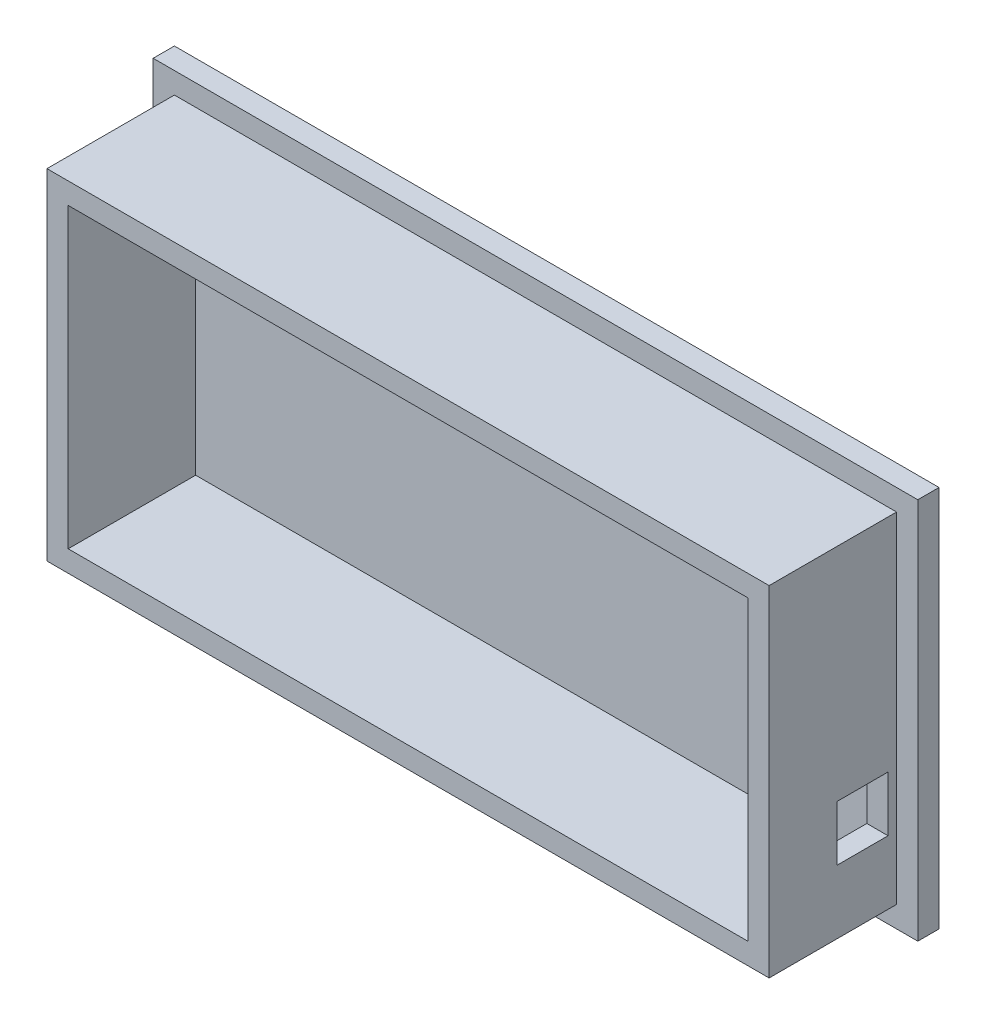
SolidWorks part; units mm, degrees
ref_plane "Plan de face" through (0, 0, 0) normal (0, 0, 1) x (1, 0, 0)
ref_plane "Plan de dessus" through (0, 0, 0) normal (0, 1, 0) x (1, 0, 0)
ref_plane "Plan de droite" through (0, 0, 0) normal (1, 0, 0) x (0, 0, -1)
sketch "Esquisse2" plane through (0, 0, 0) normal (0, 0, 1) x (1, 0, 0)
  line L1 (0, 0) -> (180, 0)
  line L2 (0, 0) -> (0, 90)
  line L3 (0, 90) -> (180, 90)
  line L4 (180, 0) -> (180, 90)
  dimension "D1" = 180
  dimension "D2" = 90
extrude "Boss.-Extru.2" add sketch "Esquisse2" along normal blind 5
sketch "Esquisse3" plane through (0, 0, 5) normal (0, 0, 1) x (1, 0, 0)
  line L4 (170, 80) -> (10, 80)
  line L5 (10, 80) -> (10, 10)
  line L6 (10, 10) -> (170, 10)
  line L7 (170, 10) -> (170, 80)
  line L8 (5, 85) -> (5, 5)
  line L9 (5, 5) -> (175, 5)
  line L10 (175, 5) -> (175, 85)
  line L11 (175, 85) -> (5, 85)
  line L12 (5, 85) -> (5, 5)
  line L13 (5, 5) -> (175, 5)
  line L14 (175, 5) -> (175, 85)
  line L15 (175, 85) -> (5, 85)
  dimension "D1" = 5
  dimension "D2" = 5
extrude "Boss.-Extru.3" add sketch "Esquisse3" along normal blind 30
sketch "Esquisse4" plane through (175, 0, 0) normal (1, 0, 0) x (0, 0, -1)
  line L0 (-5, 0) -> (-5, 90) construction
  line L1 (-19, 20) -> (-7, 20)
  line L2 (-19, 20) -> (-19, 33)
  line L3 (-19, 33) -> (-7, 33)
  line L4 (-7, 20) -> (-7, 33)
  line L5 (-35, 5) -> (-5, 5) construction
  dimension "D1" = 2
  dimension "D2" = 15
  dimension "D3" = 13
  dimension "D4" = 12
extrude "Enlèv. mat.-Extru.1" cut sketch "Esquisse4" against normal up to surface (5 mm away) up to face at (170, 45, 20)
